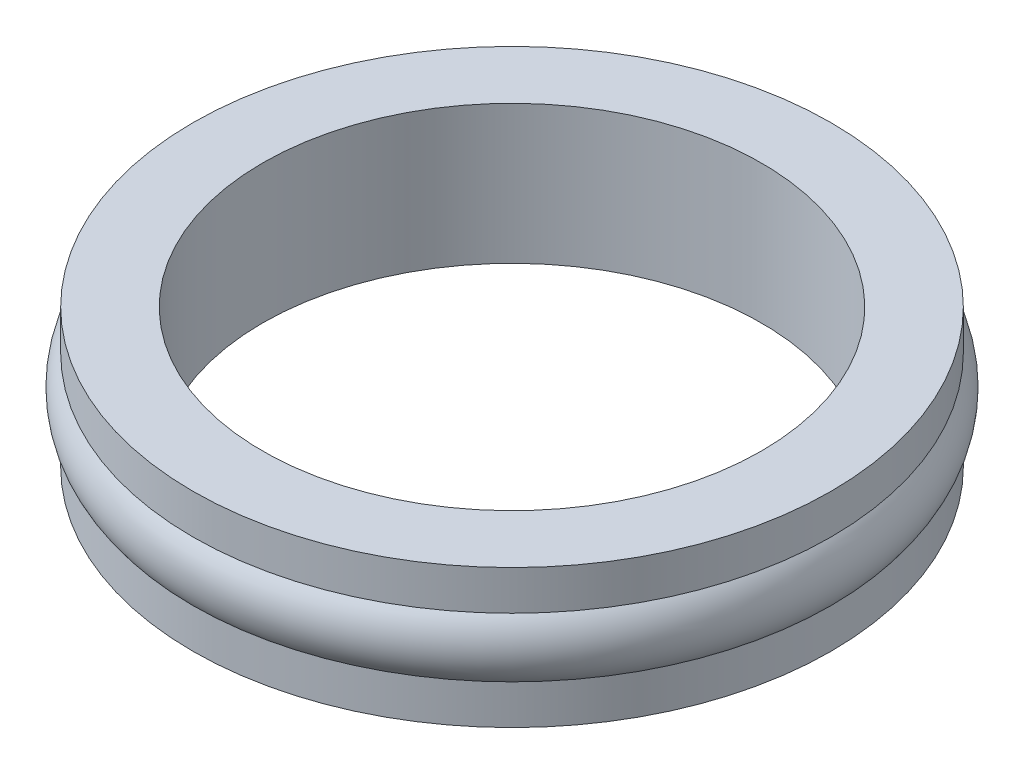
SolidWorks part; units mm, degrees
material "1023 Carbon Steel Sheet (SS)"
ref_plane "Front Plane" through (0, 0, 0) normal (0, 0, 1) x (1, 0, 0)
ref_plane "Top Plane" through (0, 0, 0) normal (0, 1, 0) x (1, 0, 0)
ref_plane "Right Plane" through (0, 0, 0) normal (1, 0, 0) x (0, 0, -1)
sketch "Sketch1" plane through (0, 0, 0) normal (0, 0, 1) x (1, 0, 0)
  line L0 (0, -133.9954) -> (0, 6565.7766) construction
  line L1 (8.06, -0.2857) -> (8.06, -1.2857)
  line L2 (6.3, 2.2143) -> (8.06, 2.2143)
  line L3 (6.3, 2.2143) -> (6.3, -1.2857)
  line L4 (6.3, -1.2857) -> (8.06, -1.2857)
  line L5 (8.06, 2.2143) -> (8.06, 1.2143)
  arc A0 (8.06, 1.2143) -> (8.06, -0.2857) centre (7.1233, 0.4643) cw
  point P10 (8.3233, 0.4643)
  point P12 (6.3, 0.4643)
  dimension "D4" = 1.5
  dimension "D5" = 1.2
  dimension "D1" = 12.6
  dimension "D2" = 16.12
  dimension "D3" = 3.5
revolve "Revolve1" add sketch "Sketch1" angle 360 about L0
